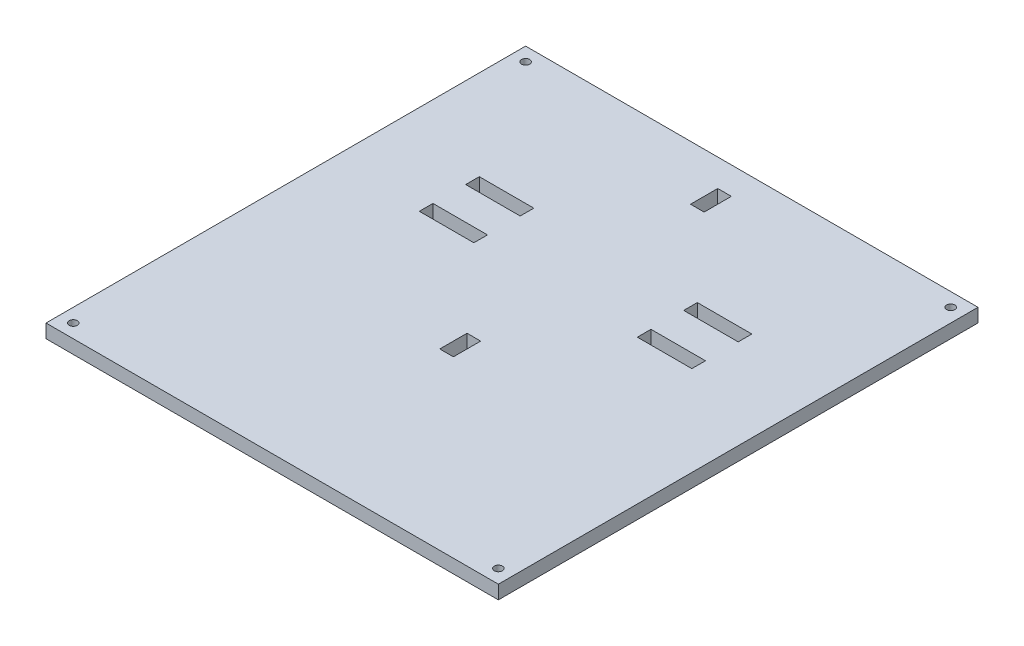
SolidWorks part; units mm, degrees
ref_plane "前视基准面" through (0, 0, 0) normal (0, 0, 1) x (1, 0, 0)
ref_plane "上视基准面" through (0, 0, 0) normal (0, 1, 0) x (1, 0, 0)
ref_plane "右视基准面" through (0, 0, 0) normal (1, 0, 0) x (0, 0, -1)
sketch "草图1" plane through (0, 0, 0) normal (0, 1, 0) x (1, 0, 0)
  line L0 (-32.4974, 80.5222) -> (199.0386, 80.5222) construction
  line L1 (5, 157.8667) -> (5, -64.3704) construction
  line L2 (0, 0) -> (0, 116)
  line L3 (80.5, 120.5222) -> (85.5, 120.5222)
  line L4 (166, 0) -> (166, 116)
  line L5 (-32.4974, 75.5222) -> (199.0386, 75.5222) construction
  line L6 (-28.8974, 63.5222) -> (199.0386, 63.5222) construction
  line L7 (-28.8974, 58.5222) -> (199.0386, 58.5222) construction
  line L8 (83, 132.5542) -> (83, 8.7542) construction
  line L9 (53, 165.3181) -> (53, -21.37) construction
  line L10 (113, -21.37) -> (113, 168.692) construction
  line L11 (0, 116) -> (0, 130.5222)
  line L12 (53, 80.5222) -> (33, 80.5222)
  line L13 (53, 80.5222) -> (53, 75.5222)
  line L14 (53, 75.5222) -> (33, 75.5222)
  line L15 (33, 80.5222) -> (33, 75.5222)
  line L16 (53, 63.5222) -> (33, 63.5222)
  line L17 (53, 63.5222) -> (53, 58.5222)
  line L18 (53, 58.5222) -> (33, 58.5222)
  line L19 (33, 63.5222) -> (33, 58.5222)
  line L20 (113, 80.5222) -> (133, 80.5222)
  line L21 (113, 80.5222) -> (113, 75.5222)
  line L22 (113, 75.5222) -> (133, 75.5222)
  line L23 (133, 80.5222) -> (133, 75.5222)
  line L24 (113, 63.5222) -> (133, 63.5222)
  line L25 (113, 63.5222) -> (113, 58.5222)
  line L26 (113, 58.5222) -> (133, 58.5222)
  line L27 (133, 63.5222) -> (133, 58.5222)
  line L28 (0, 130.5222) -> (166, 130.5222)
  line L29 (166, 130.5222) -> (166, 116)
  line L30 (166, 0) -> (166, -45.4778)
  line L31 (166, -45.4778) -> (0, -45.4778)
  line L32 (0, -45.4778) -> (0, 0)
  line L33 (80.5, 120.5222) -> (80.5, 110.5222)
  line L34 (80.5, 110.5222) -> (85.5, 110.5222)
  line L35 (85.5, 120.5222) -> (85.5, 110.5222)
  line L36 (80.5, 28.5222) -> (85.5, 28.5222)
  line L37 (80.5, 28.5222) -> (80.5, 18.5222)
  line L38 (80.5, 18.5222) -> (85.5, 18.5222)
  line L39 (85.5, 28.5222) -> (85.5, 18.5222)
  line L40 (-24.1122, -40.4778) -> (251.6881, -40.4778) construction
  line L41 (161, -64.3704) -> (161, 157.8667) construction
  line L42 (189.475, 125.5222) -> (-32.4974, 125.5222) construction
  circle A0 centre (5, 125.5222) radius 1.5
  circle A1 centre (161, 125.5222) radius 1.5
  circle A2 centre (5, -40.4778) radius 1.5
  circle A3 centre (161, -40.4778) radius 1.5
  dimension "D1" = 5
  dimension "D2" = 5
  dimension "D3" = 83
  dimension "D4" = 166
  dimension "D5" = 116
  dimension "D6" = 12
  dimension "D7" = 60
  dimension "D8" = 30
  dimension "D9" = 50
  dimension "D10" = 104
  dimension "D11" = 176
  dimension "D12" = 5
  dimension "D13" = 5
  dimension "D14" = 10
  dimension "D15" = 2.5
  dimension "D16" = 30
  dimension "D17" = 10
  dimension "D18" = 2.5
  dimension "D19" = 30
  dimension "D20" = 5
  dimension "D21" = 5
  dimension "D22" = 5
  dimension "D23" = 5
extrude "凸台-拉伸1" add sketch "草图1" along normal blind 5
